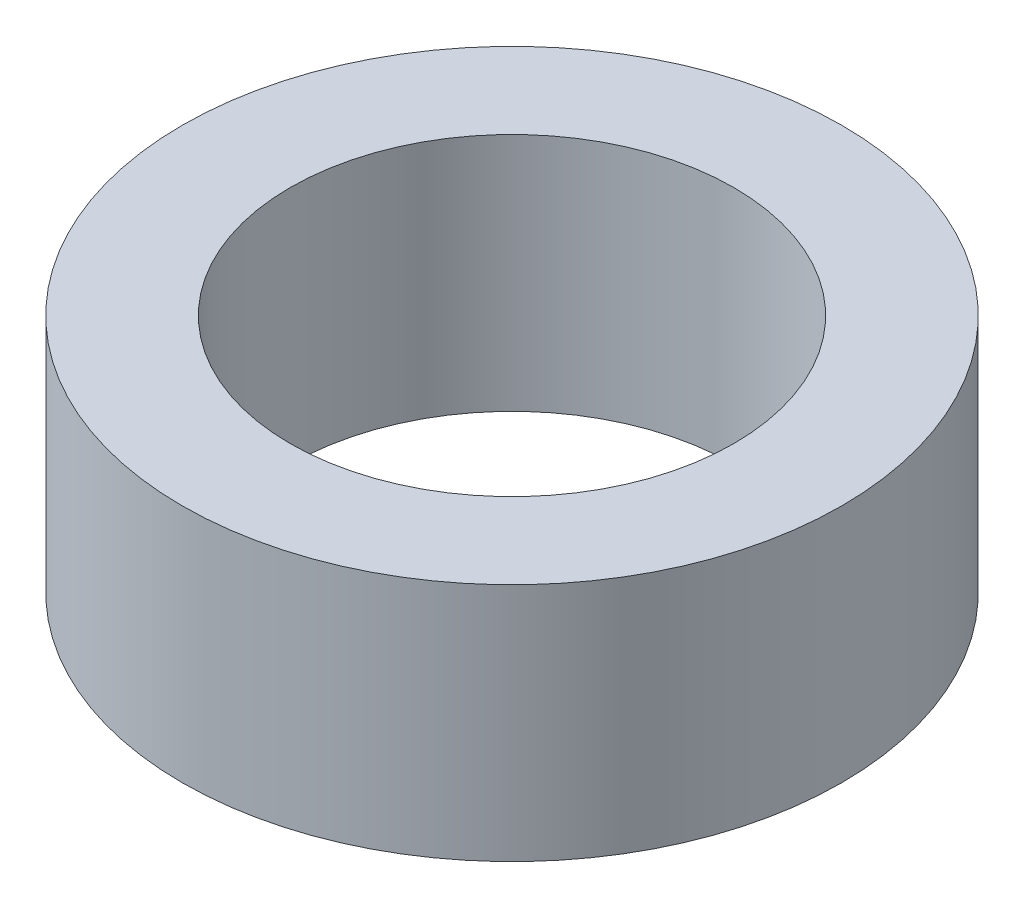
SolidWorks part; units mm, degrees
ref_plane "Front Plane" through (0, 0, 0) normal (0, 0, 1) x (1, 0, 0)
ref_plane "Top Plane" through (0, 0, 0) normal (0, 1, 0) x (1, 0, 0)
ref_plane "Right Plane" through (0, 0, 0) normal (1, 0, 0) x (0, 0, -1)
sketch "Sketch1" plane through (0, 0, 0) normal (0, 1, 0) x (1, 0, 0)
  circle A0 centre (0, 0) radius 4.699
  circle A1 centre (0, 0) radius 6.985
  dimension "D1" = 9.398
  dimension "D2" = 13.97
extrude "Boss-Extrude1" add sketch "Sketch1" along normal blind 5.08
